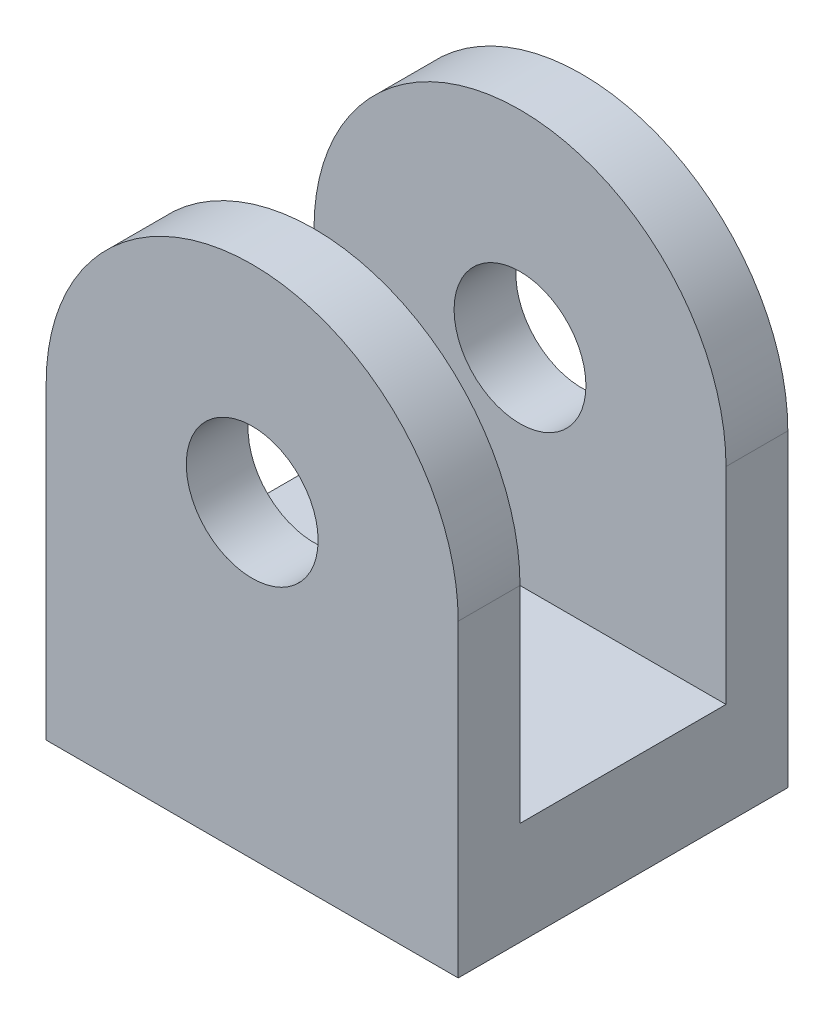
SolidWorks part; units mm, degrees
ref_plane "正面" through (0, 0, 0) normal (0, 0, 1) x (1, 0, 0)
ref_plane "平面" through (0, 0, 0) normal (0, 1, 0) x (1, 0, 0)
ref_plane "右側面" through (0, 0, 0) normal (1, 0, 0) x (0, 0, -1)
sketch "ｽｹｯﾁ2" plane through (0, 0, 0) normal (0, 1, 0) x (1, 0, 0)
  line L1 (0, 0) -> (10, 0)
  line L2 (0, 0) -> (0, 8)
  line L3 (0, 8) -> (10, 8)
  line L4 (10, 0) -> (10, 8)
  dimension "D1" = 8
  dimension "D2" = 10
extrude "ﾎﾞｽ - 押し出し1" add sketch "ｽｹｯﾁ2" along normal blind 12.5 contours L3 L4 L1 L2
sketch "ｽｹｯﾁ3" plane through (0, 12.5, 0) normal (0, 1, 0) x (1, 0, 0)
  line L0 (0, 4) -> (10, 4) construction
  line L1 (0, 0) -> (0, 8) construction
  line L2 (10, 0) -> (10, 8) construction
  line L4 (0, 6.5) -> (10, 6.5)
  line L5 (0, 6.5) -> (0, 1.5)
  line L6 (0, 1.5) -> (10, 1.5)
  line L7 (10, 6.5) -> (10, 1.5)
  point P10 (0, 4)
  dimension "D1" = 5
extrude "ｶｯﾄ - 押し出し1" cut sketch "ｽｹｯﾁ3" against normal blind 10
sketch "ｽｹｯﾁ4" plane through (0, 0, 0) normal (0, 0, 1) x (1, 0, 0)
  line L0 (0, 12.5) -> (10, 12.5) construction
  circle A0 centre (5, 7.5) radius 1.6
  point P5 (5, 12.5)
  dimension "D1" = 3.2
  dimension "D2" = 5
extrude "ｶｯﾄ - 押し出し2" cut sketch "ｽｹｯﾁ4" against normal through all
sketch "ｽｹｯﾁ5" plane through (0, 0, 0) normal (0, 0, 1) x (1, 0, 0)
  line L0 (0, 7.5) -> (0, 0)
  line L1 (0, 0) -> (10, 0)
  line L2 (10, 0) -> (10, 7.5)
  arc A0 (10, 7.5) -> (0, 7.5) centre (5, 7.5) ccw
extrude "ｶｯﾄ - 押し出し3" cut sketch "ｽｹｯﾁ5" against normal through all flip side to cut
